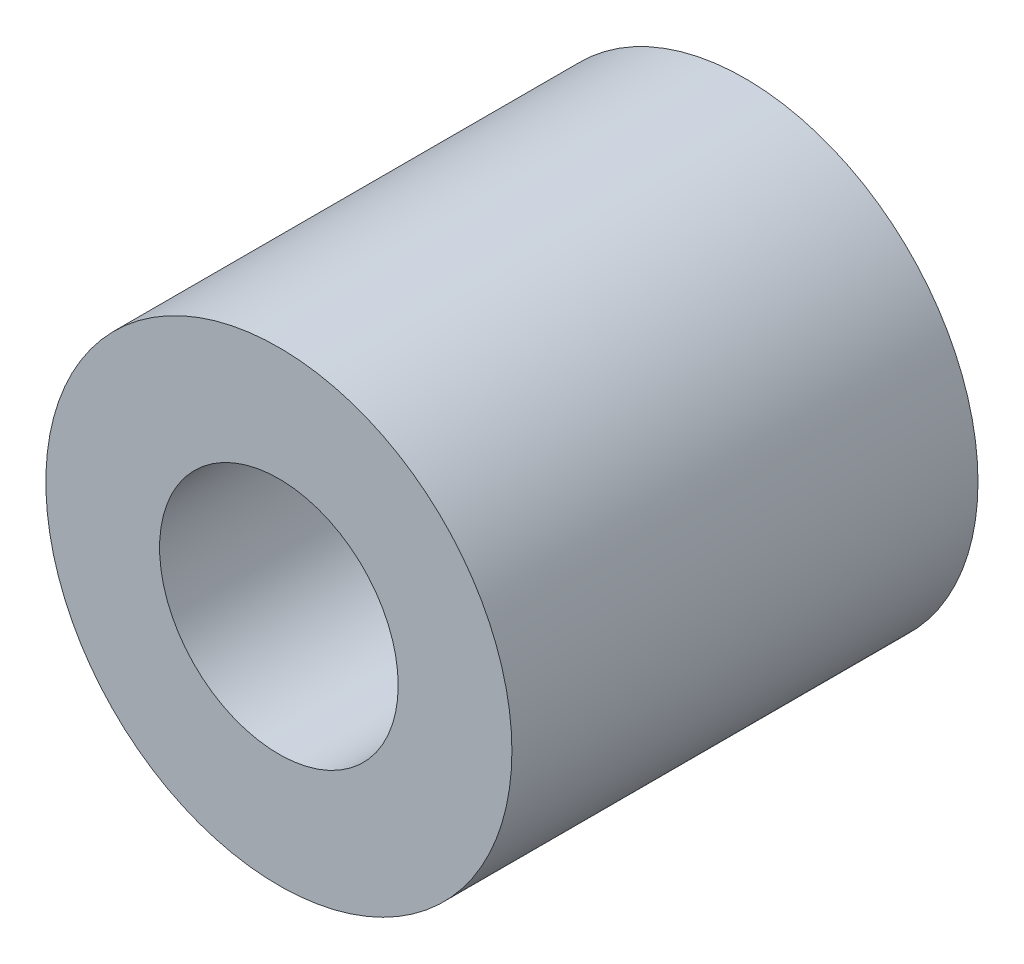
SolidWorks part; units mm, degrees
ref_plane "Front Plane" through (0, 0, 0) normal (0, 0, 1) x (1, 0, 0)
ref_plane "Top Plane" through (0, 0, 0) normal (0, 1, 0) x (1, 0, 0)
ref_plane "Right Plane" through (0, 0, 0) normal (1, 0, 0) x (0, 0, -1)
sketch "Sketch1" plane through (0, 0, 0) normal (0, 0, 1) x (1, 0, 0)
  circle A0 centre (0, 0) radius 1.5875
  circle A1 centre (0, 0) radius 0.8128
  dimension "OD" = 3.175
  dimension "ID" = 1.6256
extrude "Extrude1" add sketch "Sketch1" along normal mid plane 3.175
sketch "Sketch2" plane through (0, 0, 0) normal (1, 0, 0) x (0, 0, -1)
  line L0 (-1.5875, -0.8128) -> (1.5875, -0.8128) construction
  line L3 (1.5875, 0.8128) -> (-1.5875, 0.8128) construction
  line L5 (-1.5875, -0.8128) -> (1.5875, -0.8128)
  line L6 (1.5875, 0.8128) -> (-1.5875, 0.8128)
sketch "Sketch4" plane through (0, 0, 1.5875) normal (0, 0, 1) x (1, 0, 0)
  line L0 (0, 0) -> (-0.5747, 0.5747)
  line L1 (0, -5.2388) -> (0, 5.2388) construction
  circle A0 centre (0, 0) radius 0.8128 construction
  dimension "D1" = 45
